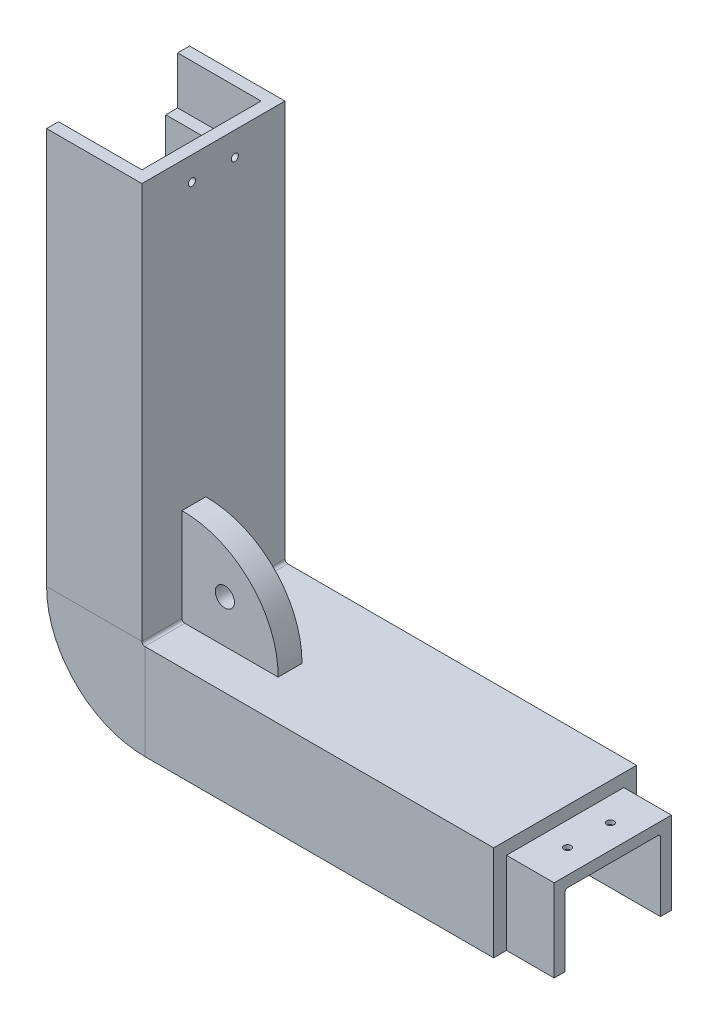
SolidWorks part; units mm, degrees
ref_plane "Front Plane" through (0, 0, 0) normal (0, 0, 1) x (1, 0, 0)
ref_plane "Top Plane" through (0, 0, 0) normal (0, 1, 0) x (1, 0, 0)
ref_plane "Right Plane" through (0, 0, 0) normal (1, 0, 0) x (0, 0, -1)
sketch "Sketch3" plane through (0, 0, 0) normal (0, 1, 0) x (1, 0, 0)
  line L1 (0, -20.955) -> (0, 20.955) construction
  line L3 (0, 16.625) -> (-25.4, 16.625)
  line L4 (-25.4, 16.625) -> (-25.4, 10.275)
  line L5 (-25.4, 10.275) -> (-6.985, 10.275)
  line L6 (-6.35, 9.64) -> (-6.35, -14.49)
  line L7 (0, -21.475) -> (-25.4, -21.475)
  line L8 (-25.4, -21.475) -> (-25.4, -15.125)
  line L9 (-25.4, -15.125) -> (-6.985, -15.125)
  line L10 (0, 16.625) -> (0, -21.475)
  arc A0 (-6.35, 9.64) -> (-6.985, 10.275) centre (-6.985, 9.64) ccw
  arc A1 (-6.35, -14.49) -> (-6.985, -15.125) centre (-6.985, -14.49) cw
  point P14 (-6.35, 10.275)
  point P17 (-6.35, -15.125)
  dimension "D7" = 0.635
  dimension "D1" = 6.35
  dimension "D2" = 6.35
  dimension "D3" = 19.05
  dimension "D4" = 6.35
  dimension "D5" = 19.05
  dimension "D6" = 25.4
sketch "Sketch4" plane through (0, 0, 0) normal (0, 0, 1) x (1, 0, 0)
  line L8 (0, 0) -> (0, -92.964)
  line L9 (0.762, -93.726) -> (93.726, -93.726)
  arc A4 (0, -92.964) -> (0.762, -93.726) centre (0.762, -92.964) ccw
  dimension "D2" = 92.964
  dimension "D1" = 92.964
sweep "Sweep1" add profiles "Sketch3" path "Sketch4"
sketch "Sketch6" plane through (93.726, 0, 0) normal (1, 0, 0) x (0, 0, -1)
  line L2 (-18.046, -97.155) -> (13.196, -97.155)
  line L6 (10.275, -119.126) -> (10.275, -100.711)
  line L8 (9.64, -100.076) -> (-14.49, -100.076)
  line L10 (-15.125, -100.711) -> (-15.125, -119.126)
  line L12 (10.275, -119.126) -> (13.196, -119.126)
  line L13 (16.625, -119.126) -> (10.275, -119.126) construction
  line L14 (13.196, -119.126) -> (13.196, -97.155)
  line L15 (-15.125, -119.126) -> (-18.046, -119.126)
  line L16 (-15.125, -119.126) -> (-21.475, -119.126) construction
  line L17 (-18.046, -119.126) -> (-18.046, -97.155)
  arc A0 (-14.49, -100.076) -> (-15.125, -100.711) centre (-14.49, -100.711) ccw
  arc A2 (-14.49, -100.076) -> (-15.125, -100.711) centre (-14.49, -100.711) ccw construction
  arc A3 (9.64, -100.076) -> (10.275, -100.711) centre (9.64, -100.711) cw
  arc A4 (10.275, -100.711) -> (9.64, -100.076) centre (9.64, -100.711) ccw construction
  dimension "D1" = 2.921
  dimension "D2" = 2.921
  dimension "D3" = 2.921
extrude "Boss-Extrude2" add sketch "Sketch6" along normal blind 12.7
sketch "Sketch7" plane through (0, 0, 0) normal (0, 1, 0) x (1, 0, 0)
  line L0 (-25.4, 13.45) -> (-25.4, 16.625)
  line L1 (-25.4, 16.625) -> (-25.4, 10.275) construction
  line L2 (-25.4, 16.625) -> (0, 16.625)
  line L3 (0, 16.625) -> (0, -21.475)
  line L4 (0, -21.475) -> (-25.4, -21.475)
  line L5 (-25.4, -21.475) -> (-25.4, -18.3)
  line L6 (-25.4, -21.475) -> (-25.4, -15.125) construction
  line L7 (-25.4, -18.3) -> (-3.175, -18.3)
  line L8 (-3.175, -18.3) -> (-3.175, 13.45)
  line L9 (-3.175, 13.45) -> (-25.4, 13.45)
  dimension "D1" = 3.175
extrude "Boss-Extrude3" add sketch "Sketch7" along normal blind 12.7
sketch "Sketch8" plane through (0, -100.076, 0) normal (0, -1, 0) x (1, 0, 0)
  line L1 (0.762, 15.125) -> (106.426, 15.125) construction
  line L2 (106.426, 14.49) -> (106.426, -9.64) construction
  line L4 (0.762, -10.275) -> (106.426, -10.275) construction
  circle A0 centre (100.076, 8.14) radius 0.9525
  circle A1 centre (100.076, -3.29) radius 0.9525
  dimension "D1" = 6.985
  dimension "D3" = 6.985
  dimension "D5" = 1.905
  dimension "D6" = 1.905
  dimension "D2" = 6.35
  dimension "D4" = 6.35
extrude "Cut-Extrude1" cut sketch "Sketch8" against normal through all
sketch "Sketch9" plane through (-3.175, 0, 0) normal (-1, 0, 0) x (0, 0, 1)
  line L0 (-13.45, 12.7) -> (18.3, 12.7) construction
  line L3 (-10.275, 0) -> (-10.275, -92.964) construction
  line L4 (15.125, 0) -> (15.125, -92.964) construction
  circle A0 centre (-3.29, 6.35) radius 0.9525
  circle A1 centre (8.14, 6.35) radius 0.9525
  dimension "D1" = 6.35
  dimension "D5" = 1.905
  dimension "D6" = 1.905
  dimension "D2" = 6.35
  dimension "D3" = 6.985
  dimension "D4" = 6.985
extrude "Cut-Extrude2" cut sketch "Sketch9" against normal through all
ref_plane "Plane--rods" through (0, 0, 7.62) normal (0, 0, 1) x (1, 0, 0)
sketch "Sketch12" plane through (0, 0, 7.62) normal (0, 0, 1) x (1, 0, 0)
  line L1 (0.762, -93.726) -> (93.726, -93.726) construction
  line L4 (0.762, -119.126) -> (0.762, -93.726) construction
  line L5 (0, 12.7) -> (0, -92.964) construction
  line L6 (0.762, -93.726) -> (25.6222, -93.726)
  line L7 (0, -68.1038) -> (0, -92.964)
  arc A0 (0, -92.964) -> (0.762, -93.726) centre (0.762, -92.964) ccw construction
  arc A3 (0, -92.964) -> (0.762, -93.726) centre (0.762, -92.964) ccw
  circle A4 centre (11.43, -82.296) radius 2.5527
  arc A6 (0, -68.1038) -> (25.6222, -93.726) centre (0.2232, -93.5028) cw
extrude "Boss-Extrude10" add sketch "Sketch12" along normal mid plane 6.35
hole_wizard "CSK for #6 Flat Head Machine Screw (100)1" positions "Sketch13" profile "Sketch14" countersink size "#6" standard "Progressive"
sketch "Sketch13" plane through (0, -100.076, 0) normal (0, -1, 0) x (-1, 0, 0)
  point P0 (-100.076, 3.29)
sketch "Sketch14" plane through (100.076, -100.076, -3.29) normal (1, 0, 0) x (0, 0, -1)
  line L0 (0, 0) -> (0, 2.4108)
  line L1 (0, 2.4108) -> (1.8986, 1.27)
  line L2 (1.8986, 1.27) -> (1.8986, 1.38)
  line L3 (1.8986, 1.38) -> (3.5433, 0)
  line L5 (3.5433, 0) -> (0, 0)
  line L6 (-1.8986, 1.38) -> (-3.5433, 0) construction
  line L10 (0, 2.4108) -> (-1.8986, 1.27) construction
  line L11 (0, -6.35) -> (0, 107.95) construction
  dimension "Hole Dia." = 3.7973
  dimension "Hole Depth" = 1.27
  dimension "Near C'Sink Dia." = 7.0866
  dimension "Near C'Sink Angle" = 100
  dimension "Drill Angle" = 118
hole_wizard "CSK for #6 Flat Head Machine Screw (100)2" positions "Sketch15" profile "Sketch16" countersink size "#6" standard "Progressive"
sketch "Sketch15" plane through (0, -100.076, 0) normal (0, -1, 0) x (-1, 0, 0)
  point P0 (-100.076, -8.14)
sketch "Sketch16" plane through (100.076, -100.076, 8.14) normal (1, 0, 0) x (0, 0, -1)
  line L0 (0, 0) -> (0, 2.4108)
  line L1 (0, 2.4108) -> (1.8986, 1.27)
  line L2 (1.8986, 1.27) -> (1.8986, 1.38)
  line L3 (1.8986, 1.38) -> (3.5433, 0)
  line L5 (3.5433, 0) -> (0, 0)
  line L6 (-1.8986, 1.38) -> (-3.5433, 0) construction
  line L10 (0, 2.4108) -> (-1.8986, 1.27) construction
  line L11 (0, -6.35) -> (0, 107.95) construction
  dimension "Hole Dia." = 3.7973
  dimension "Hole Depth" = 1.27
  dimension "Near C'Sink Dia." = 7.0866
  dimension "Near C'Sink Angle" = 100
  dimension "Drill Angle" = 118
ref_plane "Plane2" through (0, 0, 2.425) normal (0, 0, -1) x (-1, 0, 0)
ref_plane "Plane--midpoint" through (0, 0, 2.425) normal (0, 0, -1) x (-1, 0, 0)
